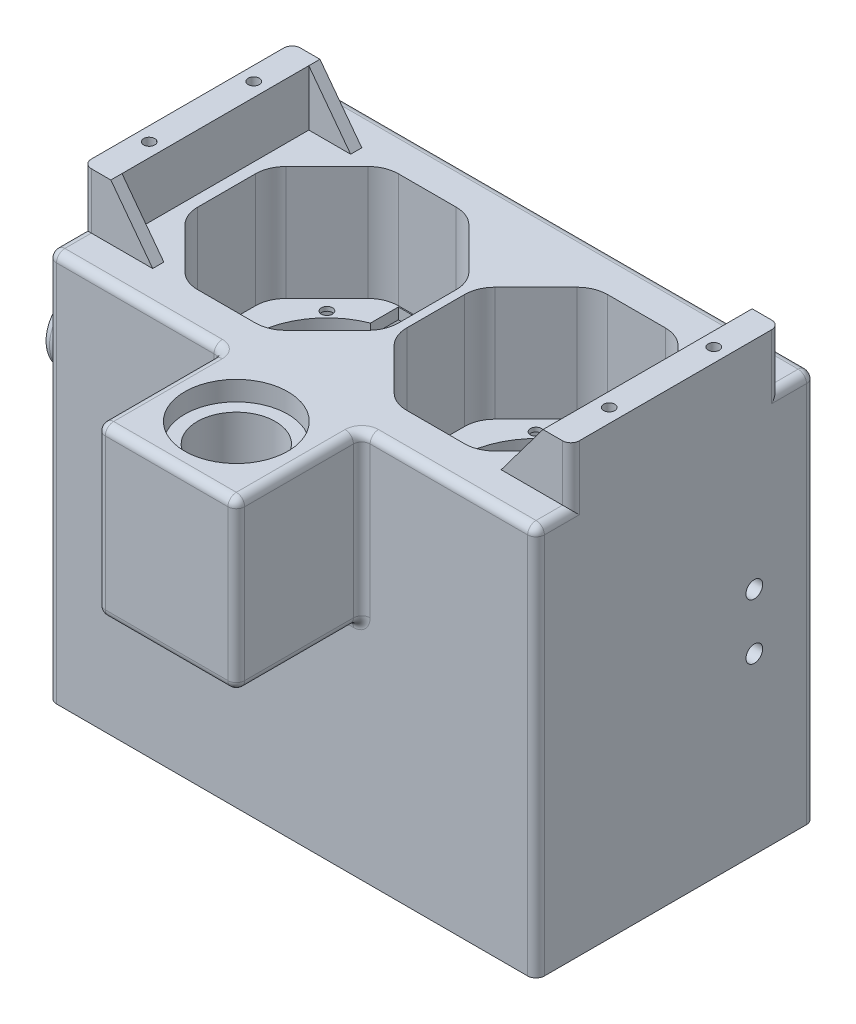
SolidWorks part; units mm, degrees
ref_plane "Front Plane" through (0, 0, 0) normal (0, 0, 1) x (1, 0, 0)
ref_plane "Top Plane" through (0, 0, 0) normal (0, 1, 0) x (1, 0, 0)
ref_plane "Right Plane" through (0, 0, 0) normal (1, 0, 0) x (0, 0, -1)
sketch "Sketch1" plane through (0, 0, 0) normal (0, 1, 0) x (1, 0, 0)
  line L0 (0, 0) -> (-79291.0816, 0) construction
  line L1 (0, 0) -> (0, -79291.0816) construction
  line L3 (-87.5, 50) -> (87.5, 50)
  line L4 (-87.5, 50) -> (-87.5, -50)
  line L5 (-87.5, -50) -> (87.5, -50)
  line L6 (87.5, 50) -> (87.5, -50)
  line L7 (-87.5, 50) -> (87.5, -50) construction
  line L8 (-87.5, -50) -> (87.5, 50) construction
  point P5 (0, 0)
  dimension "D1" = 175
  dimension "D2" = 100
extrude "Boss-Extrude1" add sketch "Sketch1" along normal blind 45
sketch "Sketch2" plane through (0, 45, 0) normal (0, 1, 0) x (1, 0, 0)
  line L0 (0, 0) -> (-50000, 0) construction
  line L1 (0, 0) -> (0, -50000) construction
  line L3 (-87.5, 50) -> (-87.5, -50) construction
  line L4 (-37.5, -12.3814) -> (-37.5, -50012.3814) construction
  line L5 (-50, 0) -> (-50050, 0) construction
  line L8 (-27.1447, 35) -> (-47.8553, 35) construction
  line L9 (-54.9264, 32.0711) -> (-69.5711, 17.4264) construction
  line L10 (-72.5, 10.3553) -> (-72.5, -10.3553) construction
  line L11 (-2.5, 10.3553) -> (-2.5, -10.3553) construction
  line L12 (-20.0736, 32.0711) -> (-5.4289, 17.4264) construction
  line L13 (-20.0736, -32.0711) -> (-5.4289, -17.4264) construction
  line L14 (-54.9264, -32.0711) -> (-69.5711, -17.4264) construction
  line L15 (-27.1447, -35) -> (-47.8553, -35) construction
  line L16 (50, 0) -> (-49950, 0) construction
  line L25 (-19.3665, -32.7782) -> (-4.7218, -18.1335)
  line L26 (-1.5, 10.3553) -> (-1.5, -10.3553)
  line L27 (-19.3665, 32.7782) -> (-4.7218, 18.1335)
  line L28 (-27.1447, 36) -> (-47.8553, 36)
  line L29 (-55.6335, 32.7782) -> (-70.2782, 18.1335)
  line L30 (-73.5, 10.3553) -> (-73.5, -10.3553)
  line L31 (-55.6335, -32.7782) -> (-70.2782, -18.1335)
  line L32 (-27.1447, -36) -> (-47.8553, -36)
  line L41 (37.5, 0) -> (37.5, -50000) construction
  line L42 (87.5, -50) -> (87.5, 50) construction
  line L44 (47.8553, 35) -> (27.1447, 35) construction
  line L45 (20.0736, 32.0711) -> (5.4289, 17.4264) construction
  line L46 (2.5, 10.3553) -> (2.5, -10.3553) construction
  line L47 (72.5, 10.3553) -> (72.5, -10.3553) construction
  line L48 (54.9264, 32.0711) -> (69.5711, 17.4264) construction
  line L49 (54.9264, -32.0711) -> (69.5711, -17.4264) construction
  line L50 (20.0736, -32.0711) -> (5.4289, -17.4264) construction
  line L51 (47.8553, -35) -> (27.1447, -35) construction
  line L52 (55.6335, -32.7782) -> (70.2782, -18.1335)
  line L53 (73.5, 10.3553) -> (73.5, -10.3553)
  line L54 (55.6335, 32.7782) -> (70.2782, 18.1335)
  line L55 (47.8553, 36) -> (27.1447, 36)
  line L56 (19.3665, 32.7782) -> (4.7218, 18.1335)
  line L57 (1.5, 10.3553) -> (1.5, -10.3553)
  line L58 (19.3665, -32.7782) -> (4.7218, -18.1335)
  line L59 (47.8553, -36) -> (27.1447, -36)
  circle A0 centre (-37.5, 0) radius 35 construction
  arc A10 (-69.5711, 17.4264) -> (-72.5, 10.3553) centre (-62.5, 10.3553) ccw construction
  arc A11 (-69.5711, -17.4264) -> (-72.5, -10.3553) centre (-62.5, -10.3553) cw construction
  arc A12 (-54.9264, -32.0711) -> (-47.8553, -35) centre (-47.8553, -25) ccw construction
  arc A13 (-20.0736, -32.0711) -> (-27.1447, -35) centre (-27.1447, -25) cw construction
  arc A14 (-5.4289, -17.4264) -> (-2.5, -10.3553) centre (-12.5, -10.3553) ccw construction
  arc A15 (-2.5, 10.3553) -> (-5.4289, 17.4264) centre (-12.5, 10.3553) ccw construction
  arc A16 (-20.0736, 32.0711) -> (-27.1447, 35) centre (-27.1447, 25) ccw construction
  arc A17 (-47.8553, 35) -> (-54.9264, 32.0711) centre (-47.8553, 25) ccw construction
  arc A18 (-4.7218, -18.1335) -> (-1.5, -10.3553) centre (-12.5, -10.3553) ccw
  arc A19 (-1.5, 10.3553) -> (-4.7218, 18.1335) centre (-12.5, 10.3553) ccw
  arc A20 (-19.3665, 32.7782) -> (-27.1447, 36) centre (-27.1447, 25) ccw
  arc A21 (-47.8553, 36) -> (-55.6335, 32.7782) centre (-47.8553, 25) ccw
  arc A22 (-70.2782, 18.1335) -> (-73.5, 10.3553) centre (-62.5, 10.3553) ccw
  arc A23 (-70.2782, -18.1335) -> (-73.5, -10.3553) centre (-62.5, -10.3553) cw
  arc A24 (-55.6335, -32.7782) -> (-47.8553, -36) centre (-47.8553, -25) ccw
  arc A25 (-19.3665, -32.7782) -> (-27.1447, -36) centre (-27.1447, -25) cw
  circle A34 centre (37.5, 0) radius 35 construction
  arc A35 (5.4289, 17.4264) -> (2.5, 10.3553) centre (12.5, 10.3553) ccw construction
  arc A36 (5.4289, -17.4264) -> (2.5, -10.3553) centre (12.5, -10.3553) cw construction
  arc A37 (20.0736, -32.0711) -> (27.1447, -35) centre (27.1447, -25) ccw construction
  arc A38 (54.9264, -32.0711) -> (47.8553, -35) centre (47.8553, -25) cw construction
  arc A39 (69.5711, -17.4264) -> (72.5, -10.3553) centre (62.5, -10.3553) ccw construction
  arc A40 (72.5, 10.3553) -> (69.5711, 17.4264) centre (62.5, 10.3553) ccw construction
  arc A41 (54.9264, 32.0711) -> (47.8553, 35) centre (47.8553, 25) ccw construction
  arc A42 (27.1447, 35) -> (20.0736, 32.0711) centre (27.1447, 25) ccw construction
  arc A43 (70.2782, -18.1335) -> (73.5, -10.3553) centre (62.5, -10.3553) ccw
  arc A44 (73.5, 10.3553) -> (70.2782, 18.1335) centre (62.5, 10.3553) ccw
  arc A45 (55.6335, 32.7782) -> (47.8553, 36) centre (47.8553, 25) ccw
  arc A46 (27.1447, 36) -> (19.3665, 32.7782) centre (27.1447, 25) ccw
  arc A47 (4.7218, 18.1335) -> (1.5, 10.3553) centre (12.5, 10.3553) ccw
  arc A48 (4.7218, -18.1335) -> (1.5, -10.3553) centre (12.5, -10.3553) cw
  arc A49 (19.3665, -32.7782) -> (27.1447, -36) centre (27.1447, -25) ccw
  arc A50 (55.6335, -32.7782) -> (47.8553, -36) centre (47.8553, -25) cw
  point P19 (-37.5, -35)
  point P26 (-37.5, 35)
  point P29 (-2.5, 0)
  point P30 (-72.5, 0)
  point P37 (37.5, -35)
  point P44 (37.5, 35)
  point P47 (72.5, 0)
  point P48 (2.5, 0)
  point P51 (2.5, 14.4975)
  point P54 (2.5, -14.4975)
  point P57 (23.0025, -35)
  point P60 (51.9975, -35)
  point P63 (72.5, -14.4975)
  point P66 (72.5, 14.4975)
  point P71 (-72.5, 14.4975)
  point P74 (-72.5, -14.4975)
  point P77 (-51.9975, -35)
  point P80 (-23.0025, -35)
  point P83 (-2.5, -14.4975)
  point P86 (-2.5, 14.4975)
  point P89 (-23.0025, 35)
  point P92 (-51.9975, 35)
  point P117 (51.9975, 35)
  point P120 (23.0025, 35)
  dimension "D1" = 70
  dimension "D3" = 50
  dimension "D4" = 70
  dimension "D5" = 50
  dimension "D8" = 10
  dimension "D9" = 10
  dimension "D7" = 1
  dimension "D10" = 1
extrude "Cut-Extrude1" cut sketch "Sketch2" against normal blind 41
sketch "Sketch3" plane through (0, 45, 0) normal (0, 1, 0) x (1, 0, 0)
  line L0 (0, 0) -> (-50000, 0) construction
  line L1 (0, 0) -> (0, -50000) construction
  line L2 (-87.5, 50) -> (-87.5, -50) construction
  line L4 (-37.5, 0) -> (-37.5, -50000) construction
  line L5 (-50, 0) -> (-50050, 0) construction
  line L6 (-27.5, 35.6174) -> (-47.5, 35.6174)
  line L7 (-47.5, 35.6174) -> (-47.5, 25.6174)
  line L8 (-27.5, 35.6174) -> (-27.5, 25.6174)
  line L9 (87.5, -50) -> (87.5, 50) construction
  line L11 (50, 0) -> (-49950, 0) construction
  line L12 (37.5, 0) -> (37.5, -50000) construction
  line L13 (47.5, 35.6174) -> (27.5, 35.6174)
  line L14 (27.5, 35.6174) -> (27.5, 25.6174)
  line L15 (47.5, 35.6174) -> (47.5, 25.6174)
  arc A0 (-47.5, 25.6174) -> (-27.5, 25.6174) centre (-37.5, 0) ccw
  arc A1 (27.5, 25.6174) -> (47.5, 25.6174) centre (37.5, 0) ccw
  point P20 (-37.5, 35.6174)
  point P34 (37.5, 35.6174)
  dimension "D1" = 50
  dimension "D3" = 55
  dimension "D6" = 55
  dimension "D7" = 50
  dimension "D4" = 10
  dimension "D5" = 10
  dimension "D9" = 10
  dimension "D10" = 10
extrude "Cut-Extrude2" cut sketch "Sketch3" against normal through all
sketch "Sketch4" plane through (0, 0, 0) normal (0, -1, 0) x (1, 0, 0)
  line L0 (0, 0) -> (-50000, 0) construction
  line L1 (0, 0) -> (0, -50000) construction
  line L2 (77.5, -40) -> (77.5, 40)
  line L3 (77.5, 40) -> (-77.5, 40)
  line L4 (-77.5, 40) -> (-77.5, -40)
  line L5 (-77.5, -40) -> (77.5, -40)
  line L6 (87.5, -50) -> (87.5, 50)
  line L7 (87.5, 50) -> (-87.5, 50)
  line L8 (-87.5, 50) -> (-87.5, -50)
  line L9 (-87.5, -50) -> (87.5, -50)
  line L10 (87.5, -50) -> (87.5, 50)
  line L11 (87.5, 50) -> (-87.5, 50)
  line L12 (-87.5, 50) -> (-87.5, -50)
  line L13 (-87.5, -50) -> (87.5, -50)
  dimension "D1" = 0
  dimension "D2" = 10
extrude "Boss-Extrude2" add sketch "Sketch4" along normal blind 95
sketch "Sketch5" plane through (0, -95, 0) normal (0, -1, 0) x (1, 0, 0)
  line L0 (0, 0) -> (-50000, 0) construction
  line L1 (0, 0) -> (0, -50000) construction
  line L2 (-77.5, 40) -> (-87.5, 50) construction
  circle A0 centre (-82.5, 45) radius 2.5
  circle A1 centre (82.5, 45) radius 2.5
  circle A2 centre (82.5, -45) radius 2.5
  circle A3 centre (-82.5, -45) radius 2.5
  dimension "D1" = 5
extrude "Cut-Extrude3" cut sketch "Sketch5" against normal blind 5
sketch "Sketch6" plane through (0, -95, 0) normal (0, -1, 0) x (1, 0, 0)
  line L0 (0, 0) -> (-50000, 0) construction
  line L1 (0, 0) -> (0, -50000) construction
  circle A0 centre (-82.5, 45) radius 2
  circle A1 centre (82.5, 45) radius 2
  circle A2 centre (82.5, -45) radius 2
  circle A3 centre (-82.5, -45) radius 2
  dimension "D1" = 4
extrude "Cut-Extrude4" cut sketch "Sketch6" against normal blind 15
sketch "Sketch7" plane through (0, 0, 0) normal (0, -1, 0) x (1, 0, 0)
  line L0 (0, 0) -> (-50000, 0) construction
  line L1 (0, 0) -> (0, -50000) construction
  line L2 (-37.5, 0) -> (-37.5, -50000) construction
  line L3 (-43.75, 6.25) -> (-35399.0891, 35361.5891) construction
  line L4 (-16.7551, 18.4995) -> (-19.0005, 20.7449)
  line L5 (-55.9995, 20.7449) -> (-56.8214, 23.8121)
  line L6 (-56.8214, 23.8121) -> (-59.8886, 24.634)
  line L7 (-59.8886, 24.634) -> (-62.134, 22.3886)
  line L8 (-62.134, 22.3886) -> (-61.3121, 19.3214)
  line L9 (-61.3121, 19.3214) -> (-58.2449, 18.4995)
  line L10 (-58.2449, 18.4995) -> (-55.9995, 20.7449)
  line L11 (-13.6879, 19.3214) -> (-16.7551, 18.4995)
  line L12 (-12.866, 22.3886) -> (-13.6879, 19.3214)
  line L13 (-15.1114, 24.634) -> (-12.866, 22.3886)
  line L14 (-18.1786, 23.8121) -> (-15.1114, 24.634)
  line L15 (-19.0005, 20.7449) -> (-18.1786, 23.8121)
  line L16 (-19.0005, -20.7449) -> (-18.1786, -23.8121)
  line L17 (-18.1786, -23.8121) -> (-15.1114, -24.634)
  line L18 (-15.1114, -24.634) -> (-12.866, -22.3886)
  line L19 (-12.866, -22.3886) -> (-13.6879, -19.3214)
  line L20 (-13.6879, -19.3214) -> (-16.7551, -18.4995)
  line L21 (-58.2449, -18.4995) -> (-55.9995, -20.7449)
  line L22 (-61.3121, -19.3214) -> (-58.2449, -18.4995)
  line L23 (-62.134, -22.3886) -> (-61.3121, -19.3214)
  line L24 (-59.8886, -24.634) -> (-62.134, -22.3886)
  line L25 (-56.8214, -23.8121) -> (-59.8886, -24.634)
  line L26 (-55.9995, -20.7449) -> (-56.8214, -23.8121)
  line L27 (-16.7551, -18.4995) -> (-19.0005, -20.7449)
  line L28 (16.7551, -18.4995) -> (19.0005, -20.7449)
  line L29 (55.9995, -20.7449) -> (56.8214, -23.8121)
  line L30 (56.8214, -23.8121) -> (59.8886, -24.634)
  line L31 (59.8886, -24.634) -> (62.134, -22.3886)
  line L32 (62.134, -22.3886) -> (61.3121, -19.3214)
  line L33 (61.3121, -19.3214) -> (58.2449, -18.4995)
  line L34 (58.2449, -18.4995) -> (55.9995, -20.7449)
  line L35 (13.6879, -19.3214) -> (16.7551, -18.4995)
  line L36 (12.866, -22.3886) -> (13.6879, -19.3214)
  line L37 (15.1114, -24.634) -> (12.866, -22.3886)
  line L38 (18.1786, -23.8121) -> (15.1114, -24.634)
  line L39 (19.0005, -20.7449) -> (18.1786, -23.8121)
  line L40 (19.0005, 20.7449) -> (18.1786, 23.8121)
  line L41 (18.1786, 23.8121) -> (15.1114, 24.634)
  line L42 (15.1114, 24.634) -> (12.866, 22.3886)
  line L43 (12.866, 22.3886) -> (13.6879, 19.3214)
  line L44 (13.6879, 19.3214) -> (16.7551, 18.4995)
  line L45 (58.2449, 18.4995) -> (55.9995, 20.7449)
  line L46 (61.3121, 19.3214) -> (58.2449, 18.4995)
  line L47 (62.134, 22.3886) -> (61.3121, 19.3214)
  line L48 (59.8886, 24.634) -> (62.134, 22.3886)
  line L49 (56.8214, 23.8121) -> (59.8886, 24.634)
  line L50 (55.9995, 20.7449) -> (56.8214, 23.8121)
  line L51 (16.7551, 18.4995) -> (19.0005, 20.7449)
  circle A0 centre (-37.5, 0) radius 30.5 construction
  circle A1 centre (-59.0668, 21.5668) radius 2.75 construction
  circle A2 centre (-15.9332, 21.5668) radius 2.75 construction
  circle A3 centre (-15.9332, -21.5668) radius 2.75 construction
  circle A4 centre (-59.0668, -21.5668) radius 2.75 construction
  circle A5 centre (59.0668, -21.5668) radius 2.75 construction
  circle A6 centre (15.9332, -21.5668) radius 2.75 construction
  circle A7 centre (15.9332, 21.5668) radius 2.75 construction
  circle A8 centre (59.0668, 21.5668) radius 2.75 construction
  dimension "D1" = 61
  dimension "D3" = 5.5
  dimension "D2" = 45
extrude "Cut-Extrude5" cut sketch "Sketch7" against normal blind 2.5
sketch "Sketch8" plane through (0, 0, 0) normal (0, -1, 0) x (1, 0, 0)
  line L0 (0, 0) -> (-50000, 0) construction
  line L1 (0, 0) -> (0, -50000) construction
  line L2 (-37.5, 0) -> (-37.5, -50000) construction
  line L3 (-43.75, 6.25) -> (-35399.0891, 35361.5891) construction
  circle A0 centre (-37.5, 0) radius 30.5 construction
  circle A1 centre (-59.0668, 21.5668) radius 2
  circle A2 centre (-15.9332, 21.5668) radius 2
  circle A3 centre (-15.9332, -21.5668) radius 2
  circle A4 centre (-59.0668, -21.5668) radius 2
  circle A5 centre (59.0668, -21.5668) radius 2
  circle A6 centre (15.9332, -21.5668) radius 2
  circle A7 centre (15.9332, 21.5668) radius 2
  circle A8 centre (59.0668, 21.5668) radius 2
  dimension "D1" = 61
  dimension "D3" = 4
  dimension "D2" = 45
extrude "Cut-Extrude6" cut sketch "Sketch8" against normal through all
sketch "Sketch10" plane through (87.5, 0, 0) normal (1, 0, 0) x (0, 0, -1)
  line L0 (0, 0) -> (-50000, 0) construction
  line L1 (0, 0) -> (0, -50000) construction
  line L2 (0, -22.5) -> (-50000, -22.5) construction
  line L3 (0, -12.5) -> (50000, -12.5) construction
  circle A0 centre (0, -22.5) radius 30 construction
  circle A4 centre (28.2843, -12.5) radius 3
  circle A5 centre (28.2843, -32.5) radius 3
  dimension "D2" = 60
  dimension "D4" = 6
  dimension "D1" = 22.5
  dimension "D3" = 10
extrude "Cut-Extrude7" cut sketch "Sketch10" against normal blind 30
sketch "Sketch11" plane through (77.5, 0, 0) normal (-1, 0, 0) x (0, 0, 1)
  line L0 (0, 0) -> (0, -50000) construction
  line L1 (-40, 0) -> (40, 0) construction
  line L27 (-24.2843, -14.8094) -> (-24.2843, -10.1906)
  line L28 (-24.2843, -10.1906) -> (-28.2843, -7.8812)
  line L29 (-28.2843, -7.8812) -> (-32.2843, -10.1906)
  line L30 (-32.2843, -10.1906) -> (-32.2843, -14.8094)
  line L31 (-32.2843, -14.8094) -> (-28.2843, -17.1188)
  line L32 (-28.2843, -17.1188) -> (-24.2843, -14.8094)
  line L33 (-24.2843, -34.8094) -> (-24.2843, -30.1906)
  line L34 (-24.2843, -30.1906) -> (-28.2843, -27.8812)
  line L35 (-28.2843, -27.8812) -> (-32.2843, -30.1906)
  line L36 (-32.2843, -30.1906) -> (-32.2843, -34.8094)
  line L37 (-32.2843, -34.8094) -> (-28.2843, -37.1188)
  line L38 (-28.2843, -37.1188) -> (-24.2843, -34.8094)
  circle A1 centre (-28.2843, -12.5) radius 4 construction
  circle A2 centre (-28.2843, -32.5) radius 4 construction
  point P4 (0, 0)
  dimension "D1" = 8
  dimension "D2" = 8
extrude "Cut-Extrude8" cut sketch "Sketch11" against normal blind 4
sketch "Sketch12" plane through (-87.5, 0, 0) normal (-1, 0, 0) x (0, 0, 1)
  line L0 (0, 0) -> (-50000, 0) construction
  line L1 (0, 0) -> (0, -50000) construction
  line L2 (-50, 45) -> (50, 45) construction
  circle A0 centre (0, -22.5) radius 12.5
  dimension "D1" = 25
  dimension "D2" = 67.5
extrude "Boss-Extrude4" add sketch "Sketch12" along normal blind 40
sketch "Sketch13" plane through (0, 45, 0) normal (0, 1, 0) x (1, 0, 0)
  line L0 (0, 0) -> (-50000, 0) construction
  line L1 (0, 0) -> (0, -50000) construction
  line L2 (-87.5, 50) -> (-87.5, -50) construction
  line L3 (-77.5, 37.5) -> (-87.5, 37.5)
  line L4 (-77.5, 37.5) -> (-77.5, -37.5)
  line L5 (-77.5, -37.5) -> (-87.5, -37.5)
  line L6 (-87.5, 37.5) -> (-87.5, -37.5)
  line L7 (-77.5, 37.5) -> (-87.5, -37.5) construction
  line L8 (-77.5, -37.5) -> (-87.5, 37.5) construction
  line L9 (77.5, -37.5) -> (87.5, -37.5)
  line L10 (87.5, 37.5) -> (87.5, -37.5)
  line L11 (77.5, 37.5) -> (87.5, 37.5)
  line L12 (77.5, 37.5) -> (77.5, -37.5)
  point P5 (-82.5, 0)
  dimension "D1" = 10
  dimension "D2" = 75
extrude "Boss-Extrude5" add sketch "Sketch13" along normal blind 20
sketch "Sketch14" plane through (0, 0, 37.5) normal (0, 0, 1) x (1, 0, 0)
  line L0 (0, 0) -> (-50000, 0) construction
  line L1 (0, 0) -> (0, -50000) construction
  line L2 (-77.5, 65) -> (-77.5, 45)
  line L3 (-77.5, 45) -> (-62.5, 45)
  line L4 (-87.5, 45) -> (87.5, 45) construction
  line L5 (-62.5, 45) -> (-77.5, 65)
  line L6 (77.5, 45) -> (62.5, 45)
  line L7 (77.5, 65) -> (77.5, 45)
  line L8 (62.5, 45) -> (77.5, 65)
  dimension "D1" = 15
extrude "Boss-Extrude6" add sketch "Sketch14" against normal blind 4
mirror "Mirror1" about plane through (0, 0, 0) normal (0, 0, 1) of "Boss-Extrude6"
sketch "Sketch15" plane through (0, 65, 0) normal (0, 1, 0) x (1, 0, 0)
  line L0 (0, 0) -> (-50000, 0) construction
  line L1 (0, 0) -> (0, -50000) construction
  line L2 (-82.5, 37.5) -> (-82.5, -49962.5) construction
  line L3 (-77.5, 37.5) -> (-87.5, 37.5) construction
  circle A0 centre (-82.5, 18.75) radius 2
  circle A1 centre (-82.5, -18.75) radius 2
  circle A2 centre (82.5, -18.75) radius 2
  circle A3 centre (82.5, 18.75) radius 2
  point P9 (-82.5, 37.5)
  dimension "D1" = 4
  dimension "D2" = 18.75
extrude "Cut-Extrude9" cut sketch "Sketch15" against normal blind 15
sketch "Sketch16" plane through (0, 45, 0) normal (0, 1, 0) x (1, 0, 0)
  line L0 (0, 0) -> (-50000, 0) construction
  line L1 (0, 0) -> (0, -50000) construction
  line L2 (-87.5, -50) -> (87.5, -50) construction
  line L3 (-25, -95) -> (25, -95)
  line L4 (-25, -95) -> (-25, -50)
  line L5 (-25, -50) -> (25, -50)
  line L6 (25, -95) -> (25, -50)
  line L7 (-25, -95) -> (25, -50) construction
  line L8 (-25, -50) -> (25, -95) construction
  point P5 (0, -72.5)
  dimension "D1" = 45
  dimension "D2" = 50
extrude "Boss-Extrude8" add sketch "Sketch16" against normal blind 60
sketch "Sketch17" plane through (0, 45, 0) normal (0, 1, 0) x (1, 0, 0)
  line L0 (0, 0) -> (-50000, 0) construction
  line L1 (0, 0) -> (0, -50000) construction
  line L3 (25, -50) -> (87.5, -50) construction
  circle A0 centre (0, -70) radius 18.5
  dimension "D1" = 37
  dimension "D2" = 20
extrude "Cut-Extrude10" cut sketch "Sketch17" against normal blind 7
sketch "Sketch18" plane through (0, 45, 0) normal (0, 1, 0) x (1, 0, 0)
  line L0 (0, 0) -> (0, -50000) construction
  line L1 (0, 0) -> (-50000, 0) construction
  circle A0 centre (0, -70) radius 14
  dimension "D1" = 28
extrude "Cut-Extrude11" cut sketch "Sketch18" against normal blind 25
fillet "Fillet1" radius 3 27 edges at (-87.5, 45, -43.75) (-56.25, 45, 50) (-127.5, -22.5, 12.5) (-87.5, 45, 43.75) (-87.5, 55, -37.5) (-87.5, 55, 37.5) (87.5, 45, -43.75) (87.5, 55, 37.5) (87.5, 55, -37.5) (87.5, 45, 43.75) (56.25, 45, 50) (25, -15, 72.5) (25, 15, 50) (0, -15, 95) (25, 15, 95) (-25, -15, 72.5) (-25, 15, 95) (0, -15, 50) (-25, 15, 50) (25, 45, 72.5) (-25, 45, 72.5) (0, 45, 95) (87.5, -25, 50) (-87.5, -25, 50) (-87.5, -25, -50) (87.5, -25, -50) (0, 45, -50)
